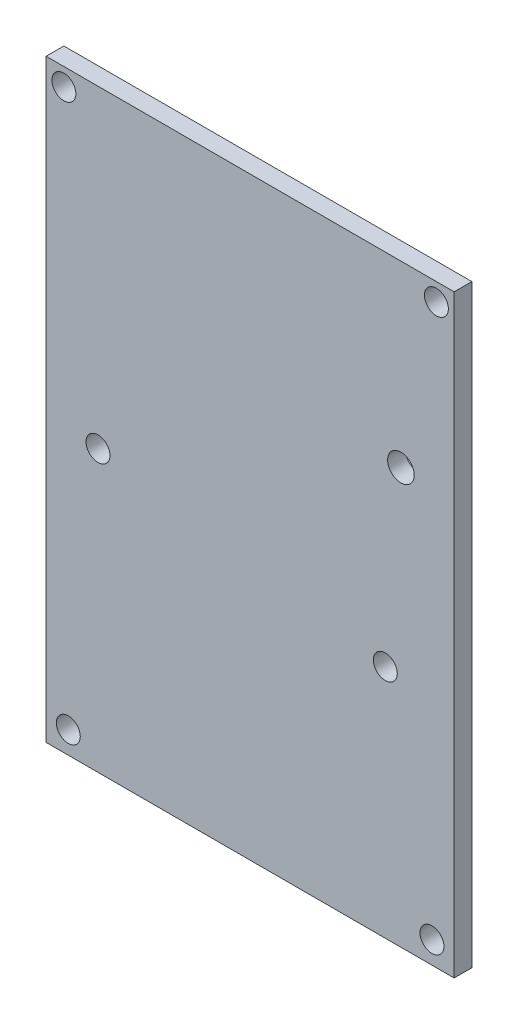
SolidWorks part; units mm, degrees
ref_plane "Front Plane" through (0, 0, 0) normal (0, 0, 1) x (1, 0, 0)
ref_plane "Top Plane" through (0, 0, 0) normal (0, 1, 0) x (1, 0, 0)
ref_plane "Right Plane" through (0, 0, 0) normal (1, 0, 0) x (0, 0, -1)
sketch "Sketch1" plane through (0, 0, 0) normal (0, 0, 1) x (1, 0, 0)
  line L1 (-23, -33.5) -> (23, -33.5)
  line L2 (-23, -33.5) -> (-23, 33.5)
  line L3 (-23, 33.5) -> (23, 33.5)
  line L4 (23, -33.5) -> (23, 33.5)
  line L5 (-23, -33.5) -> (23, 33.5) construction
  line L6 (-23, 33.5) -> (23, -33.5) construction
  point P0 (0, 0)
  dimension "D1" = 46
  dimension "D2" = 67
extrude "Boss-Extrude1" add sketch "Sketch1" along normal blind 2
hole_wizard "Ø2.7 (2.7) Diameter Hole1" positions "Sketch2" profile "Sketch3" hole size "Ø2.7" standard "DIN" end condition through all
sketch "Sketch2" plane through (0, 0, 2) normal (0, 0, 1) x (1, 0, 0)
  line L1 (-23, -33.5) -> (23, -33.5) construction
  line L2 (-23, 33.5) -> (-23, -33.5) construction
  line L6 (23, 33.5) -> (-23, 33.5) construction
  line L7 (23, -33.5) -> (23, 33.5) construction
  point P0 (-21, 31.5)
  point P2 (21, 31.5)
  point P4 (20.5, -31)
  point P6 (-20.5, -31)
  point P8 (-17.155, -1.895)
  point P10 (15.24, -6.985)
  point P57 (0, 0)
  point P58 (0, 0)
  dimension "D1" = 2
  dimension "D2" = 41
  dimension "D3" = 2.5
  dimension "D4" = 2.5
  dimension "D5" = 2
  dimension "D6" = 22.605
  dimension "D7" = 0.155
  dimension "D8" = 17.515
  dimension "D9" = 1.76
  dimension "D10" = 2
sketch "Sketch3" plane through (-21, 31.5, 2) normal (1, 0, 0) x (0, -1, 0)
  line L0 (0, 0) -> (0, 2)
  line L1 (0, 2) -> (1.35, 2)
  line L2 (1.35, 2) -> (1.35, 0)
  line L5 (1.35, 0) -> (0, 0)
  line L11 (0, -6.35) -> (0, 107.95) construction
  dimension "Thru Hole Dia." = 2.7
  dimension "Thru Hole Depth" = 2
hole_wizard "Ø3.0 (3) Diameter Hole1" positions "Sketch4" profile "Sketch5" hole size "Ø3.0" standard "DIN" end condition through all
sketch "Sketch4" plane through (0, 0, 2) normal (0, 0, 1) x (1, 0, 0)
  point P0 (17, 13.345)
  dimension "D1" = 37.845
sketch "Sketch5" plane through (17, 13.345, 2) normal (1, 0, 0) x (0, -1, 0)
  line L0 (0, 0) -> (0, 2)
  line L1 (0, 2) -> (1.5, 2)
  line L2 (1.5, 2) -> (1.5, 0)
  line L5 (1.5, 0) -> (0, 0)
  line L11 (0, -6.35) -> (0, 107.95) construction
  dimension "Thru Hole Dia." = 3
  dimension "Thru Hole Depth" = 2
equation "\"D1@Fillet5\"=\"D1@Fillet1\""
equation "\"D4@Hole locations\" = \"D3@Hole locations\""
equation "\"D3@Sketch58\"=\"SubD9HoleLeft\""
equation "\"D1@Hole locations\"=\"TopHoleLocFromTop\""
equation "\"SubD9HoleLeft\"=10.5"
equation "\"TopHoleLocFromTop\" = 1.6"
